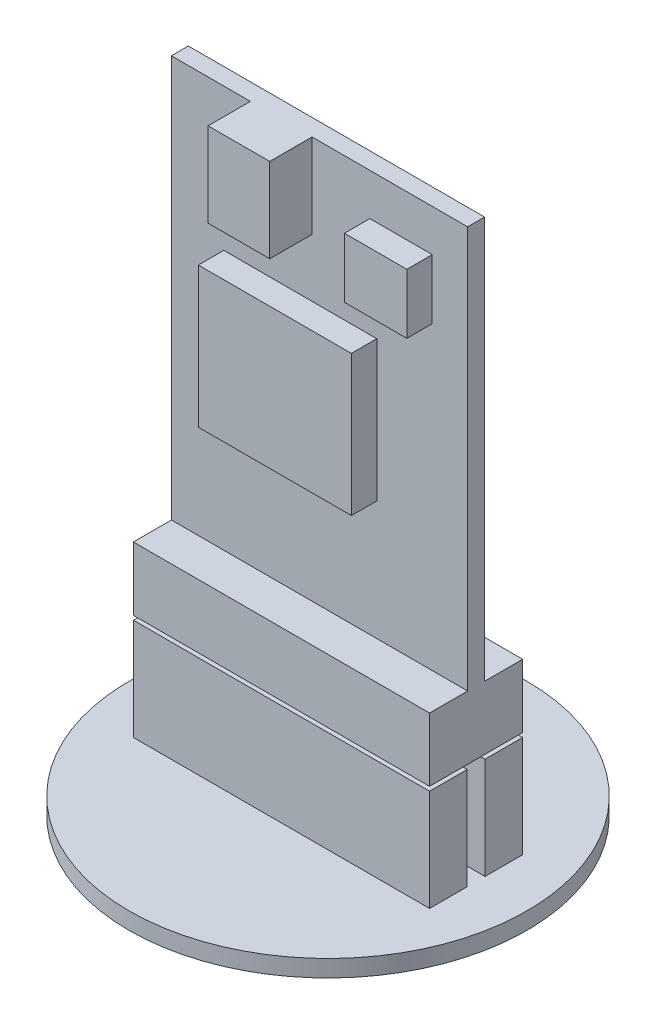
SolidWorks part; units mm, degrees
ref_plane "Front Plane" through (0, 0, 0) normal (0, 0, 1) x (1, 0, 0)
ref_plane "Top Plane" through (0, 0, 0) normal (0, 1, 0) x (1, 0, 0)
ref_plane "Right Plane" through (0, 0, 0) normal (1, 0, 0) x (0, 0, -1)
sketch "Sketch1" plane through (0, 0, 0) normal (0, 0, 1) x (1, 0, 0)
  line L1 (-7, 11) -> (7, 11)
  line L2 (-7, 11) -> (-7, -11)
  line L3 (-7, -11) -> (7, -11)
  line L4 (7, 11) -> (7, -11)
  line L5 (-7, 11) -> (7, -11) construction
  line L6 (-7, -11) -> (7, 11) construction
  point P0 (0, 0)
  dimension "D1" = 22
  dimension "D2" = 14
extrude "Boss-Extrude1" add sketch "Sketch1" along normal blind 0.8
sketch "Sketch2" plane through (0, 0, 0.8) normal (0, 0, 1) x (1, 0, 0)
  line L0 (7, -11) -> (7, 11) construction
  line L1 (-7, -11) -> (7, -11)
  line L2 (-7, -11) -> (-7, -8)
  line L3 (-7, -8) -> (7, -8)
  line L4 (7, -11) -> (7, -8)
  dimension "D1" = 3
extrude "Boss-Extrude2" add sketch "Sketch2" along normal blind 1.8 and the other way blind 2.6
sketch "Sketch3" plane through (0, 0, 0.8) normal (0, 0, 1) x (1, 0, 0)
  line L0 (7, 11) -> (-7, 11) construction
  line L1 (-3.267, 11) -> (-0.3536, 11)
  line L2 (-3.267, 11) -> (-3.267, 7.015)
  line L3 (-3.267, 7.015) -> (-0.3536, 7.015)
  line L4 (-0.3536, 11) -> (-0.3536, 7.015)
extrude "Boss-Extrude3" add sketch "Sketch3" along normal blind 2
sketch "Sketch4" plane through (0, 0, 0.8) normal (0, 0, 1) x (1, 0, 0)
  line L1 (-4.5276, 4.2715) -> (2.7043, 4.2715)
  line L2 (-4.5276, 4.2715) -> (-4.5276, -2.3662)
  line L3 (-4.5276, -2.3662) -> (2.7043, -2.3662)
  line L4 (2.7043, 4.2715) -> (2.7043, -2.3662)
  line L5 (2.3765, 9.0245) -> (5.3266, 9.0245)
  line L6 (2.3765, 9.0245) -> (2.3765, 6.1973)
  line L7 (2.3765, 6.1973) -> (5.3266, 6.1973)
  line L8 (5.3266, 9.0245) -> (5.3266, 6.1973)
extrude "Boss-Extrude4" add sketch "Sketch4" along normal blind 1.2
sketch "Sketch5" plane through (0, -11, 0) normal (0, -1, 0) x (1, 0, 0)
  line L1 (-7, 2.6) -> (7, 2.6)
  line L2 (-7, 2.6) -> (-7, 0.82)
  line L3 (-7, 0.82) -> (7, 0.82)
  line L4 (7, 2.6) -> (7, 0.82)
  line L5 (-7, 2.6) -> (-7, -1.8) construction
  line L6 (7, -1.8) -> (-7, -1.8)
  line L7 (7, -1.8) -> (7, -0.02)
  line L8 (7, -0.02) -> (-7, -0.02)
  line L9 (-7, -1.8) -> (-7, -0.02)
  dimension "D1" = 1.78
  dimension "D2" = 1.78
extrude "Boss-Extrude5" add sketch "Sketch5" along normal blind 4.8 from offset 0.2 separate body
sketch "Sketch6" plane through (0, -16, 0) normal (0, -1, 0) x (1, 0, 0)
  line L0 (-7, 2.6) -> (7, -1.8) construction
  line L1 (-7, -1.8) -> (7, 2.6) construction
  circle A0 centre (0, 0.4) radius 9.4
  point P10 (0, 0)
  dimension "D1" = 18.8
extrude "Boss-Extrude6" add sketch "Sketch6" along normal blind 0.8
